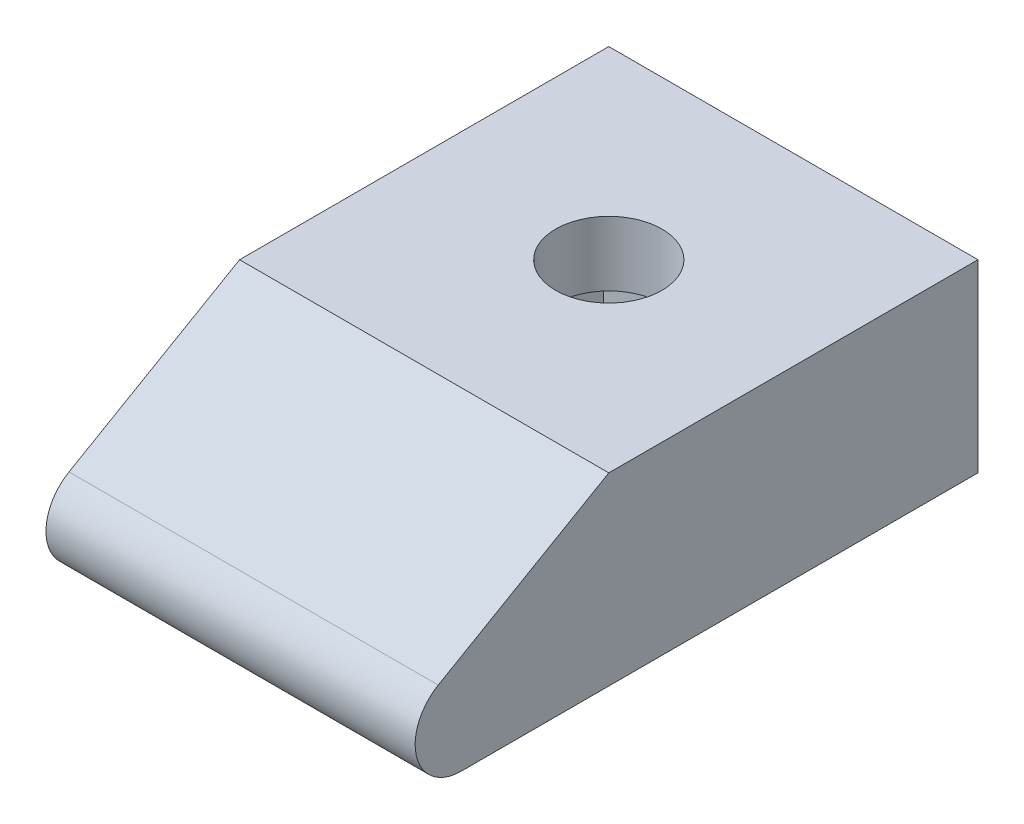
SolidWorks part; units mm, degrees
ref_plane "Front Plane" through (0, 0, 0) normal (0, 0, 1) x (1, 0, 0)
ref_plane "Top Plane" through (0, 0, 0) normal (0, 1, 0) x (1, 0, 0)
ref_plane "Right Plane" through (0, 0, 0) normal (1, 0, 0) x (0, 0, -1)
sketch "Sketch1" plane through (0, 0, 0) normal (0, 1, 0) x (1, 0, 0)
  line L1 (0, 0) -> (25.4, 0)
  line L2 (0, 0) -> (0, 25.4)
  line L3 (0, 25.4) -> (25.4, 25.4)
  line L4 (25.4, 0) -> (25.4, 25.4)
  dimension "D1" = 25.4
extrude "Boss-Extrude1" add sketch "Sketch1" along normal blind 12.7
sketch "Sketch3" plane through (0, 12.7, 0) normal (0, 1, 0) x (1, 0, 0)
  line L0 (0, 12.7) -> (25.4, 12.7) construction
  line L1 (0, 25.4) -> (0, 0) construction
  line L2 (25.4, 0) -> (25.4, 25.4) construction
  circle A0 centre (12.7, 12.7) radius 3.6576
  dimension "D1" = 7.3152
extrude "Cut-Extrude1" cut sketch "Sketch3" against normal blind 4.445
sketch "Sketch2" plane through (0, 0, 0) normal (0, -1, 0) x (1, 0, 0)
  line L0 (0, -12.7) -> (25.4, -12.7) construction
  line L1 (5.715, -6.096) -> (19.685, -6.096)
  line L2 (5.715, -6.096) -> (5.715, -19.304)
  line L3 (5.715, -19.304) -> (19.685, -19.304)
  line L4 (19.685, -6.096) -> (19.685, -19.304)
  line L5 (0, -25.4) -> (0, 0) construction
  line L6 (25.4, 0) -> (25.4, -25.4) construction
  line L7 (12.7, 0) -> (12.7, -25.4) construction
  line L8 (0, 0) -> (25.4, 0) construction
  line L9 (25.4, -25.4) -> (0, -25.4) construction
  point P10 (19.685, -12.7)
  point P17 (12.7, -6.096)
  dimension "D1" = 13.97
  dimension "D2" = 13.208
extrude "Cut-Extrude2" cut sketch "Sketch2" against normal up to surface (8.255 mm away) up to face at (12.7, 8.255, -9.0424)
sketch "Sketch4" plane through (0, 0, 0) normal (0, -1, 0) x (1, 0, 0)
  line L0 (5.715, -6.096) -> (5.715, -19.304) construction
  line L1 (5.715, -9.2075) -> (4.445, -9.2075)
  line L2 (5.715, -9.2075) -> (5.715, -16.1925)
  line L3 (5.715, -16.1925) -> (4.445, -16.1925)
  line L4 (4.445, -9.2075) -> (4.445, -16.1925)
  line L7 (0, -12.7) -> (25.4, -12.7) construction
  line L8 (12.7, 0) -> (12.7, -25.4) construction
  line L9 (12.7, 0) -> (12.7, -25.4) construction
  line L10 (19.685, -16.1925) -> (20.955, -16.1925)
  line L11 (20.955, -9.2075) -> (20.955, -16.1925)
  line L12 (19.685, -9.2075) -> (20.955, -9.2075)
  line L13 (19.685, -9.2075) -> (19.685, -16.1925)
  point P8 (4.445, -12.7)
  dimension "D1" = 6.985
  dimension "D2" = 1.27
extrude "Cut-Extrude3" cut sketch "Sketch4" against normal blind 3.175
sketch "Sketch5" plane through (0, 0, 0) normal (-1, 0, 0) x (0, 0, 1)
  line L5 (0, 0) -> (21.997, 0)
  line L6 (21.997, 0) -> (0, 12.7)
  line L7 (0, 12.7) -> (0, 0)
  line L8 (-25.4, 12.7) -> (0, 12.7) construction
  dimension "D1" = 30
extrude "Boss-Extrude2" add sketch "Sketch5" against normal up to surface (25.4 mm away) up to face at (25.4, 6.35, -12.7)
fillet "Fillet1" radius 3.175 1 edges at (12.7, 0, 21.997)
sketch "Sketch6" plane through (0, 0, 0) normal (0, -1, 0) x (1, 0, 0)
  line L0 (19.685, -6.096) -> (5.715, -6.096) construction
  line L1 (9.525, -6.096) -> (15.875, -6.096)
  line L2 (9.525, -6.096) -> (9.525, -4.5085)
  line L3 (9.525, -4.5085) -> (15.875, -4.5085)
  line L4 (15.875, -6.096) -> (15.875, -4.5085)
  line L5 (5.715, -12.7) -> (19.685, -12.7) construction
  line L6 (5.715, -6.096) -> (5.715, -19.304) construction
  line L7 (19.685, -9.2075) -> (19.685, -16.1925) construction
  line L8 (9.525, -20.8915) -> (15.875, -20.8915)
  line L9 (15.875, -19.304) -> (15.875, -20.8915)
  line L10 (9.525, -19.304) -> (15.875, -19.304)
  line L11 (9.525, -19.304) -> (9.525, -20.8915)
  point P12 (12.7, -6.096)
  point P13 (12.7, -12.7)
  dimension "D1" = 1.5875
  dimension "D2" = 6.35
extrude "Boss-Extrude3" add sketch "Sketch6" along normal blind 6.35
sketch "Sketch7" plane through (9.525, 0, 0) normal (-1, 0, 0) x (0, 0, 1)
  line L0 (-4.5085, -6.35) -> (-1.5474, 0)
  line L1 (-25.4, 0) -> (10.1478, 0) construction
  line L2 (-1.5474, 0) -> (-4.5085, 0)
  line L3 (-4.5085, 0) -> (-4.5085, -6.35)
  line L4 (-20.8915, -6.35) -> (-23.8526, 0)
  line L5 (-23.8526, 0) -> (-20.8915, 0)
  line L6 (-20.8915, 0) -> (-20.8915, -6.35)
  dimension "D1" = 25
extrude "Boss-Extrude4" add sketch "Sketch7" against normal up to surface (6.35 mm away) up to face at (15.875, -3.175, -5.3023)
ref_plane "Plane1" through (12.7, 0, 0) normal (-1, 0, 0) x (0, 0, 1)
sketch "Sketch8" plane through (12.7, 0, 0) normal (-1, 0, 0) x (0, 0, 1)
  line L0 (-19.304, 0) -> (-19.304, -4.064) construction
  line L1 (-19.304, -6.35) -> (-19.304, 0) construction
  line L2 (-19.304, -6.35) -> (-6.096, -6.35) construction
  line L3 (-12.7, -6.35) -> (-12.7, 0) construction
  line L4 (-25.4, 0) -> (10.1478, 0) construction
  circle A0 centre (-19.304, -3.2702) radius 0.7937
  circle A1 centre (-6.096, -3.2702) radius 0.7937
  dimension "D2" = 1.5875
  dimension "D1" = 4.064
extrude "Cut-Extrude4" cut sketch "Sketch8" against normal mid plane 3.175
